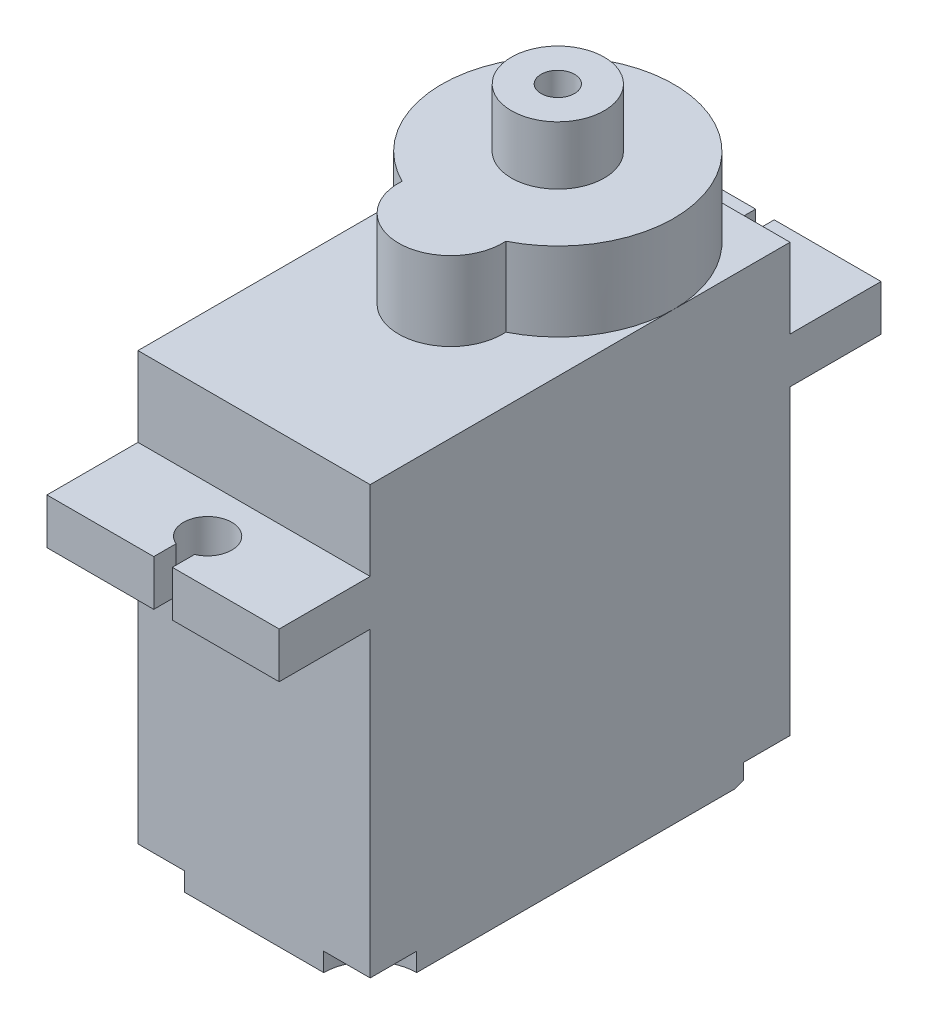
SolidWorks part; units mm, degrees
ref_plane "前视基准面" through (0, 0, 0) normal (0, 0, 1) x (1, 0, 0)
ref_plane "上视基准面" through (0, 0, 0) normal (0, 1, 0) x (1, 0, 0)
ref_plane "右视基准面" through (0, 0, 0) normal (1, 0, 0) x (0, 0, -1)
sketch "草图1" plane through (0, 0, 0) normal (1, 0, 0) x (0, 0, -1)
  line L0 (0, 19.5421) -> (0, -20.1589) construction
  line L1 (-21.5047, 0) -> (24.8692, 0) construction
  line L2 (-11.3, 4.28) -> (11.3, 4.28)
  line L3 (-11.3, 4.28) -> (-11.3, 0)
  line L4 (-11.3, -19.72) -> (11.3, -19.72)
  line L5 (11.3, 4.28) -> (11.3, 0)
  line L6 (-11.3, -2.46) -> (-11.3, -19.72)
  line L7 (-11.3, 0) -> (-16.2, 0)
  line L9 (-11.3, -2.46) -> (-16.2, -2.46)
  line L10 (-16.2, 0) -> (-16.2, -2.46)
  line L11 (11.3, 0) -> (16.2, 0)
  line L13 (11.3, -2.46) -> (16.2, -2.46)
  line L14 (16.2, 0) -> (16.2, -2.46)
  line L15 (11.3, -2.46) -> (11.3, -19.72)
  dimension "D1" = 24
  dimension "D2" = 22.6
  dimension "D3" = 32.4
  dimension "D4" = 2.46
  dimension "D5" = 6.74
extrude "凸台-拉伸1" add sketch "草图1" along normal mid plane 12.5
sketch "草图2" plane through (0, 0, 0) normal (0, 1, 0) x (1, 0, 0)
  line L0 (0, 19.6844) -> (0, -18.8436) construction
  line L1 (-16.1248, 0) -> (17.1198, 0) construction
  line L2 (6.25, 16.2) -> (-6.25, 16.2) construction
  line L4 (-0.5, 15) -> (-0.5, 16.2)
  line L5 (-0.5, 16.2) -> (0.5, 16.2)
  line L6 (0.5, 15) -> (0.5, 16.2)
  line L7 (-0.5, -15) -> (-0.5, -16.2)
  line L8 (-0.5, -16.2) -> (0.5, -16.2)
  line L9 (0.5, -15) -> (0.5, -16.2)
  arc A0 (-0.5, 15) -> (0.5, 15) centre (0, 13.8) ccw
  arc A1 (-0.5, -15) -> (0.5, -15) centre (0, -13.8) cw
  point P4 (0, 12.5)
  point P13 (0, 0)
  point P14 (0, 0)
  dimension "D1" = 2.6
  dimension "D3" = 12.5
  dimension "D2" = 1
extrude "切除-拉伸1" cut sketch "草图2" against normal blind 12.5
sketch "草图3" plane through (0, 4.28, 0) normal (0, 1, 0) x (1, 0, 0)
  line L0 (6.25, 11.3) -> (6.25, -11.3) construction
  line L1 (-6.25, 11.3) -> (-6.25, -11.3) construction
  line L2 (6.25, 11.3) -> (-6.25, 11.3) construction
  line L3 (0, 20.5537) -> (0, -26.165) construction
  line L4 (-6.25, 11.3) -> (6.25, 11.3) construction
  line L5 (-8.8354, -3.52) -> (12.7267, -3.52) construction
  arc A0 (2.7942, -0.5406) -> (-2.7942, -0.5406) centre (0, 5.05) ccw
  arc A1 (-2.7942, -0.5406) -> (2.7942, -0.5406) centre (0, -0.72) ccw
  dimension "D1" = 5.6
  dimension "D2" = 14.82
extrude "凸台-拉伸2" add sketch "草图3" along normal blind 4.24
sketch "草图4" plane through (0, 8.52, 0) normal (0, 1, 0) x (1, 0, 0)
  circle A0 centre (0, 5.05) radius 2.5
  circle A1 centre (0, 5.05) radius 0.9
  arc A2 (2.7942, -0.5406) -> (6.25, 5.05) centre (0, 5.05) ccw construction
  dimension "D1" = 5
  dimension "D2" = 1.8
extrude "凸台-拉伸3" add sketch "草图4" along normal blind 3.14
sketch "草图5" plane through (0, -19.72, 0) normal (0, -1, 0) x (1, 0, 0)
  line L0 (-10.9246, 0) -> (15.057, 0) construction
  line L1 (0, 16.6396) -> (0, -18.7058) construction
  circle A0 centre (6.25, 11.3) radius 2.5
  circle A1 centre (6.25, -11.3) radius 2.5
  circle A2 centre (-6.25, -11.3) radius 2.5
  circle A3 centre (-6.25, 11.3) radius 2.5
  dimension "D1" = 5
extrude "切除-拉伸2" cut sketch "草图5" against normal blind 1
sketch "草图6" plane through (-6.25, 0, 0) normal (-1, 0, 0) x (0, 0, 1)
  line L0 (-11.3, -18.72) -> (-11.3, -19.72)
  line L1 (-11.3, -18.72) -> (-11.3, -2.46) construction
  line L2 (-11.3, -19.72) -> (-8.3, -19.72)
  line L3 (8.8, -19.72) -> (-8.8, -19.72) construction
  line L4 (-8.3, -19.72) -> (-11.3, -18.72)
  dimension "D1" = 3
  dimension "D2" = 1
extrude "切除-拉伸3" cut sketch "草图6" against normal up to surface (12.5 mm away) up to face at (6.25, -6.5482, -0.2971)
